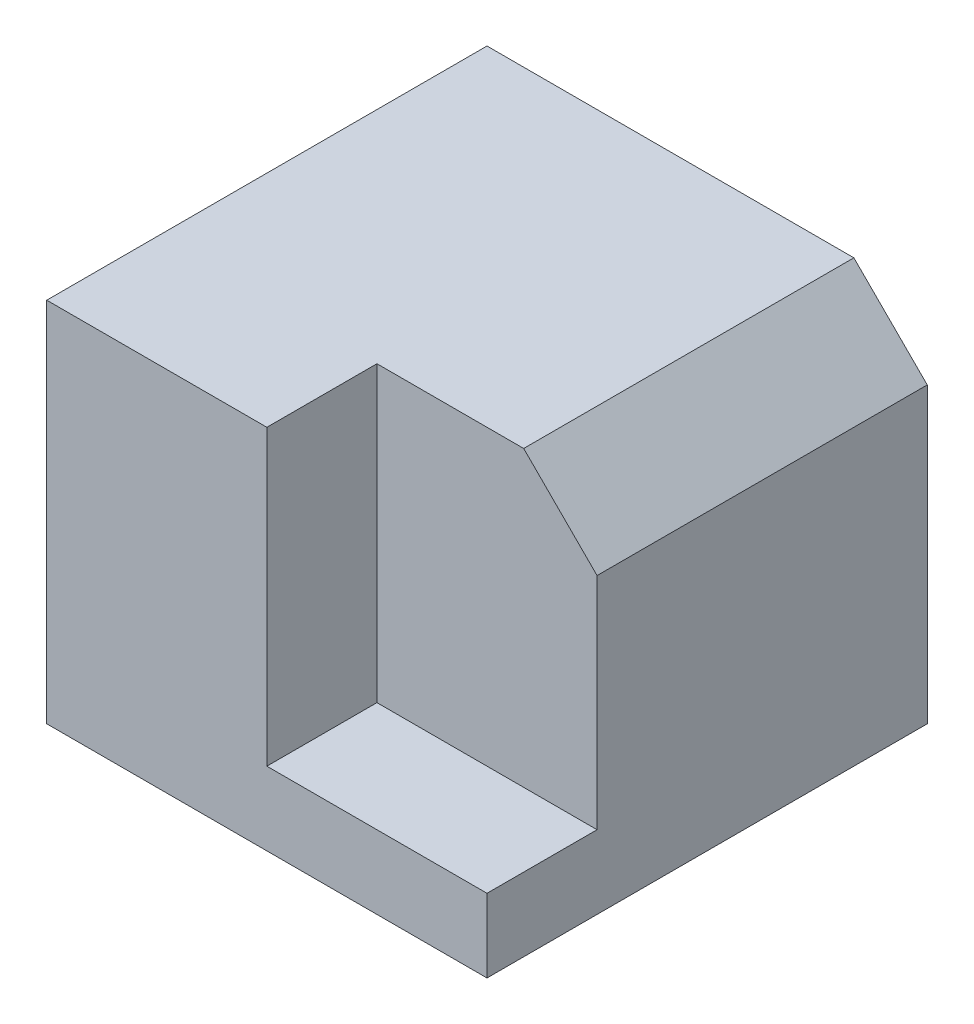
SolidWorks part; units mm, degrees
ref_plane "Front Plane" through (0, 0, 0) normal (0, 0, 1) x (1, 0, 0)
ref_plane "Top Plane" through (0, 0, 0) normal (0, 1, 0) x (1, 0, 0)
ref_plane "Right Plane" through (0, 0, 0) normal (1, 0, 0) x (0, 0, -1)
sketch "Sketch1" plane through (0, 0, 0) normal (0, 1, 0) x (1, 0, 0)
  line L1 (30, 30) -> (-30, 30)
  line L2 (30, 30) -> (30, -30)
  line L3 (30, -30) -> (-30, -30)
  line L4 (-30, 30) -> (-30, -30)
  line L5 (30, 30) -> (-30, -30) construction
  line L6 (30, -30) -> (-30, 30) construction
  point P0 (0, 0)
  dimension "D1" = 60
  dimension "D2" = 60
extrude "Extrude1" add sketch "Sketch1" along normal blind 50
sketch "Sketch2" plane through (0, 50, 0) normal (0, 1, 0) x (1, 0, 0)
  line L0 (30, -30) -> (30, 30) construction
  line L1 (30, -15) -> (0, -15)
  line L2 (30, -15) -> (30, -30)
  line L3 (30, -30) -> (0, -30)
  line L4 (0, -15) -> (0, -30)
  line L5 (-30, -30) -> (30, -30) construction
  dimension "D1" = 15
  dimension "D2" = 30
extrude "Extrude2" cut sketch "Sketch2" against normal blind 40
chamfer "Chamfer1" distance 10 angle 45 1 edges at (30, 50, -7.5)
